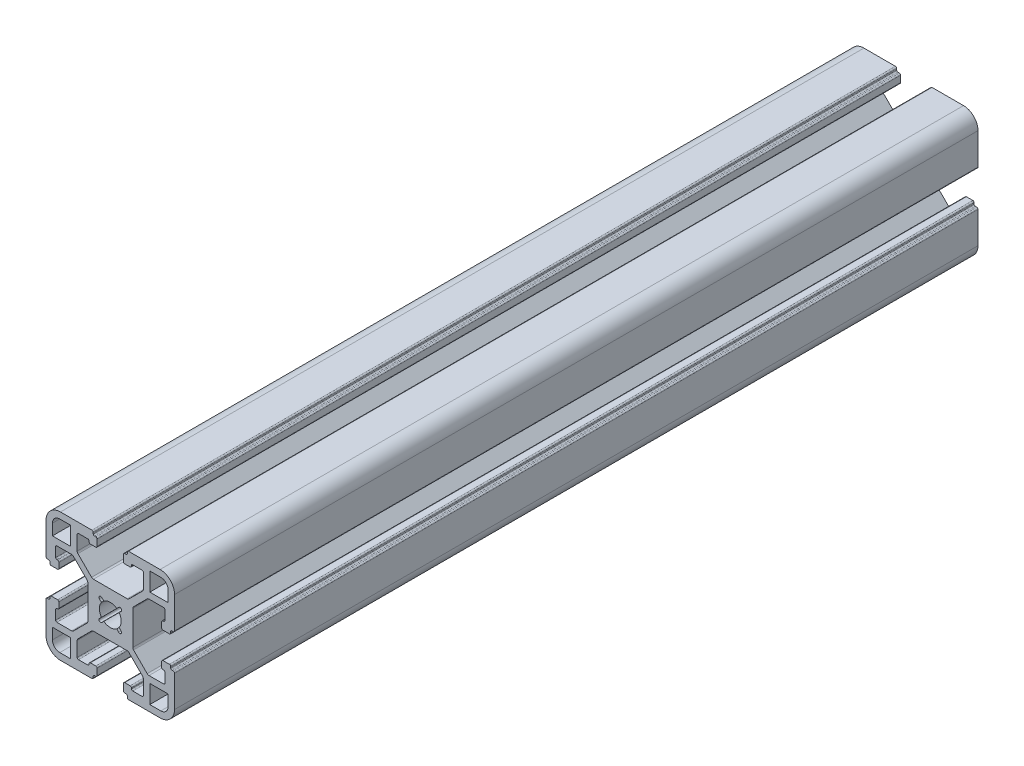
SolidWorks part; units mm, degrees
ref_plane "前视基准面" through (0, 0, 0) normal (0, 0, 1) x (1, 0, 0)
ref_plane "上视基准面" through (0, 0, 0) normal (0, 1, 0) x (1, 0, 0)
ref_plane "右视基准面" through (0, 0, 0) normal (1, 0, 0) x (0, 0, -1)
other "Configuration Table"
ref_plane "Plane1" through (0, 0, 25) normal (0, 0, 1) x (1, 0, 0)
sketch "Sketch1" plane through (0, 0, 25) normal (0, 0, 1) x (1, 0, 0)
  line L0 (18, 15.72) -> (18, 12.3)
  line L1 (18, 12.3) -> (12.3, 12.3)
  line L2 (12.3, 12.3) -> (12.3, 18)
  line L3 (12.3, 18) -> (15.72, 18)
  line L4 (-18, -15.72) -> (-18, -12.3)
  line L5 (-18, -12.3) -> (-12.3, -12.3)
  line L6 (-12.3, -12.3) -> (-12.3, -18)
  line L7 (-12.3, -18) -> (-15.72, -18)
  line L8 (-15.5, -20) -> (-5.7, -20)
  line L9 (-5.3, -19.6) -> (-5.3, -19.2)
  line L10 (-4.9, -18.8) -> (-4.5, -18.8)
  line L11 (-4.1, -18.4) -> (-4.1, -16.4)
  line L12 (-4.5, -16) -> (-6.18, -16)
  line L13 (-6.58, -16.4) -> (-6.58, -16.6)
  line L14 (-6.98, -17) -> (-9.9, -17)
  line L15 (-10.3, -16.6) -> (-10.3, -12.0456)
  line L16 (-10.0657, -11.4799) -> (-5.8201, -7.2343)
  line L17 (-5.2544, -7) -> (5.2544, -7)
  line L18 (5.8201, -7.2343) -> (10.0657, -11.4799)
  line L19 (10.3, -12.0456) -> (10.3, -16.6)
  line L20 (9.9, -17) -> (6.98, -17)
  line L21 (6.58, -16.6) -> (6.58, -16.4)
  line L22 (6.18, -16) -> (4.5, -16)
  line L23 (4.1, -16.4) -> (4.1, -18.4)
  line L24 (4.5, -18.8) -> (4.9, -18.8)
  line L25 (5.3, -19.2) -> (5.3, -19.6)
  line L26 (5.7, -20) -> (15.5, -20)
  line L27 (20, -15.5) -> (20, -5.7)
  line L28 (19.6, -5.3) -> (19.2, -5.3)
  line L29 (18.8, -4.9) -> (18.8, -4.5)
  line L30 (18.4, -4.1) -> (16.4, -4.1)
  line L31 (16, -4.5) -> (16, -6.18)
  line L32 (16.4, -6.58) -> (16.6, -6.58)
  line L33 (17, -6.98) -> (17, -9.9)
  line L34 (16.6, -10.3) -> (12.0456, -10.3)
  line L35 (11.4799, -10.0657) -> (7.2343, -5.8201)
  line L36 (7, -5.2544) -> (7, 5.2544)
  line L37 (7.2343, 5.8201) -> (11.4799, 10.0657)
  line L38 (12.0456, 10.3) -> (16.6, 10.3)
  line L39 (17, 9.9) -> (17, 6.98)
  line L40 (16.6, 6.58) -> (16.4, 6.58)
  line L41 (16, 6.18) -> (16, 4.5)
  line L42 (16.4, 4.1) -> (18.4, 4.1)
  line L43 (18.8, 4.5) -> (18.8, 4.9)
  line L44 (19.2, 5.3) -> (19.6, 5.3)
  line L45 (20, 5.7) -> (20, 15.5)
  line L46 (15.5, 20) -> (5.7, 20)
  line L47 (5.3, 19.6) -> (5.3, 19.2)
  line L48 (4.9, 18.8) -> (4.5, 18.8)
  line L49 (4.1, 18.4) -> (4.1, 16.4)
  line L50 (4.5, 16) -> (6.18, 16)
  line L51 (6.58, 16.4) -> (6.58, 16.6)
  line L52 (6.98, 17) -> (9.9, 17)
  line L53 (10.3, 16.6) -> (10.3, 12.0456)
  line L54 (10.0657, 11.4799) -> (5.8201, 7.2343)
  line L55 (5.2544, 7) -> (-5.2544, 7)
  line L56 (-5.8201, 7.2343) -> (-10.0657, 11.4799)
  line L57 (-10.3, 12.0456) -> (-10.3, 16.6)
  line L58 (-9.9, 17) -> (-6.98, 17)
  line L59 (-6.58, 16.6) -> (-6.58, 16.4)
  line L60 (-6.18, 16) -> (-4.5, 16)
  line L61 (-4.1, 16.4) -> (-4.1, 18.4)
  line L62 (-4.5, 18.8) -> (-4.9, 18.8)
  line L63 (-5.3, 19.2) -> (-5.3, 19.6)
  line L64 (-5.7, 20) -> (-15.5, 20)
  line L65 (-20, 15.5) -> (-20, 5.7)
  line L66 (-19.6, 5.3) -> (-19.2, 5.3)
  line L67 (-18.8, 4.9) -> (-18.8, 4.5)
  line L68 (-18.4, 4.1) -> (-16.4, 4.1)
  line L69 (-16, 4.5) -> (-16, 6.18)
  line L70 (-16.4, 6.58) -> (-16.6, 6.58)
  line L71 (-17, 6.98) -> (-17, 9.9)
  line L72 (-16.6, 10.3) -> (-12.0456, 10.3)
  line L73 (-11.4799, 10.0657) -> (-7.2343, 5.8201)
  line L74 (-7, 5.2544) -> (-7, -5.2544)
  line L75 (-7.2343, -5.8201) -> (-11.4799, -10.0657)
  line L76 (-12.0456, -10.3) -> (-16.6, -10.3)
  line L77 (-17, -9.9) -> (-17, -6.98)
  line L78 (-16.6, -6.58) -> (-16.4, -6.58)
  line L79 (-16, -6.18) -> (-16, -4.5)
  line L80 (-16.4, -4.1) -> (-18.4, -4.1)
  line L81 (-18.8, -4.5) -> (-18.8, -4.9)
  line L82 (-19.2, -5.3) -> (-19.6, -5.3)
  line L83 (-20, -5.7) -> (-20, -15.5)
  line L84 (2.0101, 2.7422) -> (2.6338, 3.3658)
  line L85 (3.3658, 2.6338) -> (2.7422, 2.0101)
  line L86 (2.7422, -2.0101) -> (3.3658, -2.6338)
  line L87 (2.6338, -3.3658) -> (2.0101, -2.7422)
  line L88 (-2.0101, -2.7422) -> (-2.6338, -3.3658)
  line L89 (-3.3658, -2.6338) -> (-2.7422, -2.0101)
  line L90 (-2.7422, 2.0101) -> (-3.3658, 2.6338)
  line L91 (-2.6338, 3.3658) -> (-2.0101, 2.7422)
  line L92 (15.72, -18) -> (12.3, -18)
  line L93 (12.3, -18) -> (12.3, -12.3)
  line L94 (12.3, -12.3) -> (18, -12.3)
  line L95 (18, -12.3) -> (18, -15.72)
  line L96 (-15.72, 18) -> (-12.3, 18)
  line L97 (-12.3, 18) -> (-12.3, 12.3)
  line L98 (-12.3, 12.3) -> (-18, 12.3)
  line L99 (-18, 12.3) -> (-18, 15.72)
  arc A0 (15.72, 18) -> (18, 15.72) centre (15.72, 15.72) cw
  arc A1 (-15.72, -18) -> (-18, -15.72) centre (-15.72, -15.72) cw
  arc A2 (-20, -15.5) -> (-15.5, -20) centre (-15.5, -15.5) ccw
  arc A3 (-5.7, -20) -> (-5.3, -19.6) centre (-5.7, -19.6) ccw
  arc A4 (-5.3, -19.2) -> (-4.9, -18.8) centre (-4.9, -19.2) cw
  arc A5 (-4.5, -18.8) -> (-4.1, -18.4) centre (-4.5, -18.4) ccw
  arc A6 (-4.1, -16.4) -> (-4.5, -16) centre (-4.5, -16.4) ccw
  arc A7 (-6.18, -16) -> (-6.58, -16.4) centre (-6.18, -16.4) ccw
  arc A8 (-6.58, -16.6) -> (-6.98, -17) centre (-6.98, -16.6) cw
  arc A9 (-9.9, -17) -> (-10.3, -16.6) centre (-9.9, -16.6) cw
  arc A10 (-10.3, -12.0456) -> (-10.0657, -11.4799) centre (-9.5, -12.0456) cw
  arc A11 (-5.8201, -7.2343) -> (-5.2544, -7) centre (-5.2544, -7.8) cw
  arc A12 (5.2544, -7) -> (5.8201, -7.2343) centre (5.2544, -7.8) cw
  arc A13 (10.0657, -11.4799) -> (10.3, -12.0456) centre (9.5, -12.0456) cw
  arc A14 (10.3, -16.6) -> (9.9, -17) centre (9.9, -16.6) cw
  arc A15 (6.98, -17) -> (6.58, -16.6) centre (6.98, -16.6) cw
  arc A16 (6.58, -16.4) -> (6.18, -16) centre (6.18, -16.4) ccw
  arc A17 (4.5, -16) -> (4.1, -16.4) centre (4.5, -16.4) ccw
  arc A18 (4.1, -18.4) -> (4.5, -18.8) centre (4.5, -18.4) ccw
  arc A19 (4.9, -18.8) -> (5.3, -19.2) centre (4.9, -19.2) cw
  arc A20 (5.3, -19.6) -> (5.7, -20) centre (5.7, -19.6) ccw
  arc A21 (15.5, -20) -> (20, -15.5) centre (15.5, -15.5) ccw
  arc A22 (20, -5.7) -> (19.6, -5.3) centre (19.6, -5.7) ccw
  arc A23 (19.2, -5.3) -> (18.8, -4.9) centre (19.2, -4.9) cw
  arc A24 (18.8, -4.5) -> (18.4, -4.1) centre (18.4, -4.5) ccw
  arc A25 (16.4, -4.1) -> (16, -4.5) centre (16.4, -4.5) ccw
  arc A26 (16, -6.18) -> (16.4, -6.58) centre (16.4, -6.18) ccw
  arc A27 (16.6, -6.58) -> (17, -6.98) centre (16.6, -6.98) cw
  arc A28 (17, -9.9) -> (16.6, -10.3) centre (16.6, -9.9) cw
  arc A29 (12.0456, -10.3) -> (11.4799, -10.0657) centre (12.0456, -9.5) cw
  arc A30 (7.2343, -5.8201) -> (7, -5.2544) centre (7.8, -5.2544) cw
  arc A31 (7, 5.2544) -> (7.2343, 5.8201) centre (7.8, 5.2544) cw
  arc A32 (11.4799, 10.0657) -> (12.0456, 10.3) centre (12.0456, 9.5) cw
  arc A33 (16.6, 10.3) -> (17, 9.9) centre (16.6, 9.9) cw
  arc A34 (17, 6.98) -> (16.6, 6.58) centre (16.6, 6.98) cw
  arc A35 (16.4, 6.58) -> (16, 6.18) centre (16.4, 6.18) ccw
  arc A36 (16, 4.5) -> (16.4, 4.1) centre (16.4, 4.5) ccw
  arc A37 (18.4, 4.1) -> (18.8, 4.5) centre (18.4, 4.5) ccw
  arc A38 (18.8, 4.9) -> (19.2, 5.3) centre (19.2, 4.9) cw
  arc A39 (19.6, 5.3) -> (20, 5.7) centre (19.6, 5.7) ccw
  arc A40 (20, 15.5) -> (15.5, 20) centre (15.5, 15.5) ccw
  arc A41 (5.7, 20) -> (5.3, 19.6) centre (5.7, 19.6) ccw
  arc A42 (5.3, 19.2) -> (4.9, 18.8) centre (4.9, 19.2) cw
  arc A43 (4.5, 18.8) -> (4.1, 18.4) centre (4.5, 18.4) ccw
  arc A44 (4.1, 16.4) -> (4.5, 16) centre (4.5, 16.4) ccw
  arc A45 (6.18, 16) -> (6.58, 16.4) centre (6.18, 16.4) ccw
  arc A46 (6.58, 16.6) -> (6.98, 17) centre (6.98, 16.6) cw
  arc A47 (9.9, 17) -> (10.3, 16.6) centre (9.9, 16.6) cw
  arc A48 (10.3, 12.0456) -> (10.0657, 11.4799) centre (9.5, 12.0456) cw
  arc A49 (5.8201, 7.2343) -> (5.2544, 7) centre (5.2544, 7.8) cw
  arc A50 (-5.2544, 7) -> (-5.8201, 7.2343) centre (-5.2544, 7.8) cw
  arc A51 (-10.0657, 11.4799) -> (-10.3, 12.0456) centre (-9.5, 12.0456) cw
  arc A52 (-10.3, 16.6) -> (-9.9, 17) centre (-9.9, 16.6) cw
  arc A53 (-6.98, 17) -> (-6.58, 16.6) centre (-6.98, 16.6) cw
  arc A54 (-6.58, 16.4) -> (-6.18, 16) centre (-6.18, 16.4) ccw
  arc A55 (-4.5, 16) -> (-4.1, 16.4) centre (-4.5, 16.4) ccw
  arc A56 (-4.1, 18.4) -> (-4.5, 18.8) centre (-4.5, 18.4) ccw
  arc A57 (-4.9, 18.8) -> (-5.3, 19.2) centre (-4.9, 19.2) cw
  arc A58 (-5.3, 19.6) -> (-5.7, 20) centre (-5.7, 19.6) ccw
  arc A59 (-15.5, 20) -> (-20, 15.5) centre (-15.5, 15.5) ccw
  arc A60 (-20, 5.7) -> (-19.6, 5.3) centre (-19.6, 5.7) ccw
  arc A61 (-19.2, 5.3) -> (-18.8, 4.9) centre (-19.2, 4.9) cw
  arc A62 (-18.8, 4.5) -> (-18.4, 4.1) centre (-18.4, 4.5) ccw
  arc A63 (-16.4, 4.1) -> (-16, 4.5) centre (-16.4, 4.5) ccw
  arc A64 (-16, 6.18) -> (-16.4, 6.58) centre (-16.4, 6.18) ccw
  arc A65 (-16.6, 6.58) -> (-17, 6.98) centre (-16.6, 6.98) cw
  arc A66 (-17, 9.9) -> (-16.6, 10.3) centre (-16.6, 9.9) cw
  arc A67 (-12.0456, 10.3) -> (-11.4799, 10.0657) centre (-12.0456, 9.5) cw
  arc A68 (-7.2343, 5.8201) -> (-7, 5.2544) centre (-7.8, 5.2544) cw
  arc A69 (-7, -5.2544) -> (-7.2343, -5.8201) centre (-7.8, -5.2544) cw
  arc A70 (-11.4799, -10.0657) -> (-12.0456, -10.3) centre (-12.0456, -9.5) cw
  arc A71 (-16.6, -10.3) -> (-17, -9.9) centre (-16.6, -9.9) cw
  arc A72 (-17, -6.98) -> (-16.6, -6.58) centre (-16.6, -6.98) cw
  arc A73 (-16.4, -6.58) -> (-16, -6.18) centre (-16.4, -6.18) ccw
  arc A74 (-16, -4.5) -> (-16.4, -4.1) centre (-16.4, -4.5) ccw
  arc A75 (-18.4, -4.1) -> (-18.8, -4.5) centre (-18.4, -4.5) ccw
  arc A76 (-18.8, -4.9) -> (-19.2, -5.3) centre (-19.2, -4.9) cw
  arc A77 (-19.6, -5.3) -> (-20, -5.7) centre (-19.6, -5.7) ccw
  arc A78 (2.6338, 3.3658) -> (3.3658, 2.6338) centre (2.9998, 2.9998) cw
  arc A79 (2.7422, 2.0101) -> (2.7422, -2.0101) centre (0, 0) cw
  arc A80 (3.3658, -2.6338) -> (2.6338, -3.3658) centre (2.9998, -2.9998) cw
  arc A81 (2.0101, -2.7422) -> (-2.0101, -2.7422) centre (0, 0) cw
  arc A82 (-2.6338, -3.3658) -> (-3.3658, -2.6338) centre (-2.9998, -2.9998) cw
  arc A83 (-2.7422, -2.0101) -> (-2.7422, 2.0101) centre (0, 0) cw
  arc A84 (-3.3658, 2.6338) -> (-2.6338, 3.3658) centre (-2.9998, 2.9998) cw
  arc A85 (-2.0101, 2.7422) -> (2.0101, 2.7422) centre (0, 0) cw
  arc A86 (18, -15.72) -> (15.72, -18) centre (15.72, -15.72) cw
  arc A87 (-18, 15.72) -> (-15.72, 18) centre (-15.72, 15.72) cw
extrude "Boss-Extrude1" add sketch "Sketch1" against normal blind 250
sketch "草图1" plane through (20, 0, 0) normal (1, 0, 0) x (0, 0, -1)
  line L0 (225, -5.7) -> (-25, -5.7) construction
  line L1 (225, -5.7) -> (-25, -5.7)
  line L2 (65, -5.3049) -> (45, -5.3049) construction
  line L3 (65, -5.3049) -> (45, -5.3049)
